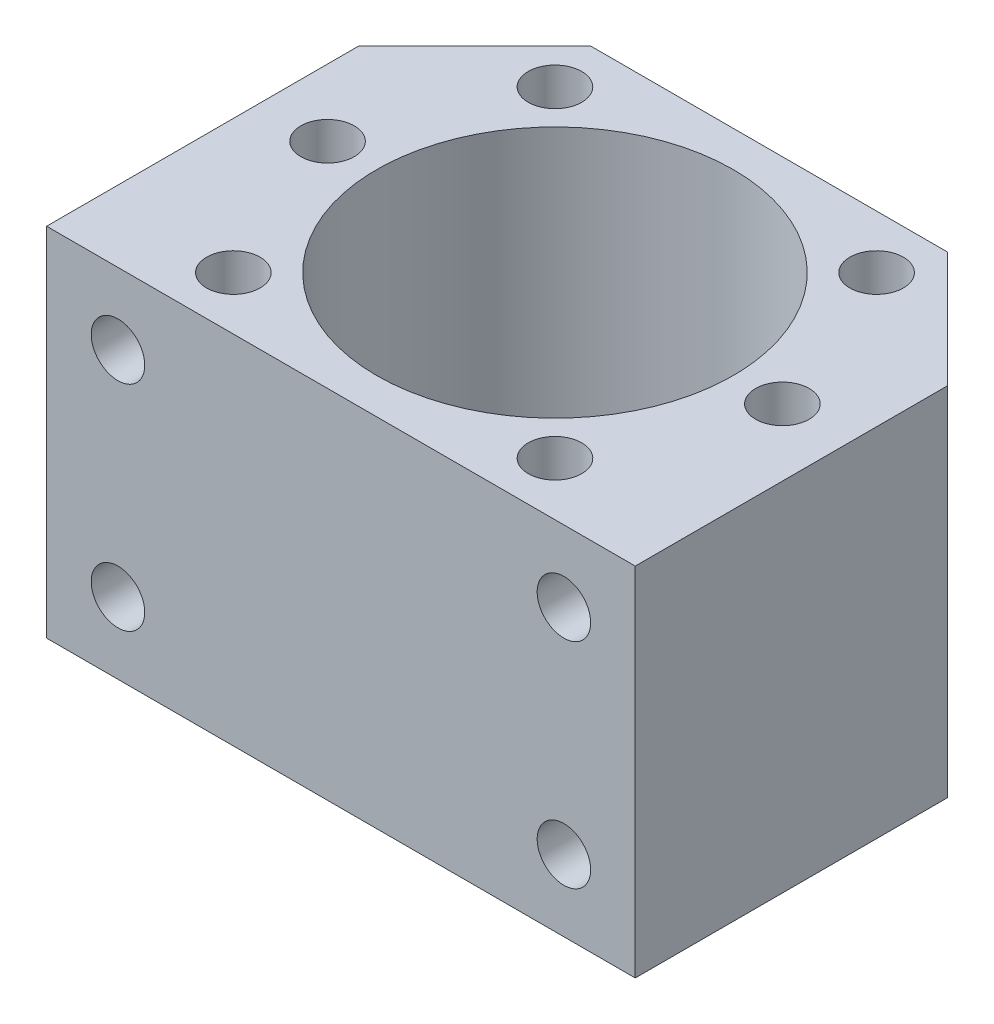
SolidWorks part; units mm, degrees
material "合金钢"
ref_plane "前视基准面" through (0, 0, 0) normal (0, 0, 1) x (1, 0, 0)
ref_plane "上视基准面" through (0, 0, 0) normal (0, 1, 0) x (1, 0, 0)
ref_plane "右视基准面" through (0, 0, 0) normal (1, 0, 0) x (0, 0, -1)
sketch "草图1" plane through (0, 0, 0) normal (0, 1, 0) x (1, 0, 0)
  line L0 (0, 51.866) -> (0, -50.4409) construction
  line L1 (-59.3894, 0) -> (53.8175, 0) construction
  line L2 (-33, -24) -> (33, -24)
  line L3 (-33, -24) -> (-33, 11)
  line L4 (-33, 11) -> (-20, 24)
  line L5 (-20, 24) -> (20, 24)
  line L6 (33, 11) -> (20, 24)
  line L7 (33, -24) -> (33, 11)
  line L8 (0, 0) -> (-18.0312, 18.0312) construction
  line L9 (0, 0) -> (-18.0312, -18.0312) construction
  circle A0 centre (0, 0) radius 20
  circle A1 centre (0, 0) radius 25.5 construction
  circle A2 centre (-25.5, 0) radius 3
  circle A3 centre (-18.0312, 18.0312) radius 3
  circle A4 centre (-18.0312, -18.0312) radius 3
  circle A5 centre (18.0312, -18.0312) radius 3
  circle A6 centre (18.0312, 18.0312) radius 3
  circle A7 centre (25.5, 0) radius 3
  point P11 (0, 24)
  point P13 (0, -24)
  dimension "D6" = 40
  dimension "D7" = 51
  dimension "D8" = 6
  dimension "D1" = 66
  dimension "D2" = 48
  dimension "D3" = 13
  dimension "D4" = 13
  dimension "D5" = 24
  dimension "D9" = 45
  dimension "D10" = 45
extrude "凸台-拉伸1" add sketch "草图1" along normal blind 40
sketch "草图2" plane through (0, 0, 24) normal (0, 0, 1) x (1, 0, 0)
  line L0 (0, 0) -> (0, 40) construction
  line L1 (-33, 0) -> (33, 0) construction
  line L2 (-33, 40) -> (33, 40) construction
  circle A0 centre (-25, 32) radius 3
  circle A1 centre (-25, 8) radius 3
  circle A2 centre (25, 8) radius 3
  circle A3 centre (25, 32) radius 3
  dimension "D3" = 6
  dimension "D1" = 8
  dimension "D2" = 24
  dimension "D4" = 50
extrude "切除-拉伸1" cut sketch "草图2" against normal blind 15
